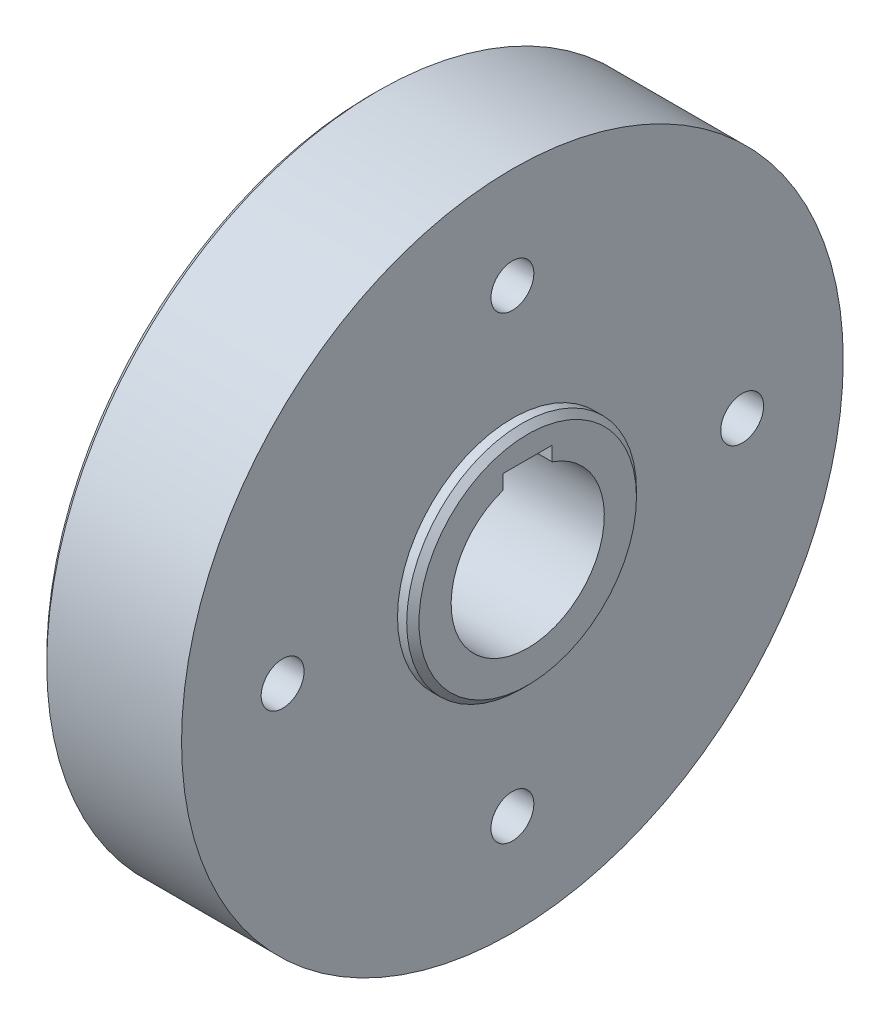
SolidWorks part; units mm, degrees
ref_plane "Front Plane" through (0, 0, 0) normal (0, 0, 1) x (1, 0, 0)
ref_plane "Top Plane" through (0, 0, 0) normal (0, 1, 0) x (1, 0, 0)
ref_plane "Right Plane" through (0, 0, 0) normal (1, 0, 0) x (0, 0, -1)
sketch "Sketch1" plane through (0, 0, 0) normal (0, 0, 1) x (1, 0, 0)
  line L0 (0, 0) -> (0, 15070.8085) construction
  line L1 (0, 0) -> (15070.8085, 0) construction
  line L2 (-40, 0) -> (40, 0)
  line L3 (-40, 25) -> (40, 25)
  line L4 (40, 108) -> (15, 108)
  line L5 (-40, 50) -> (15, 50)
  line L6 (15, 108) -> (15, 50)
  line L7 (-40, 50) -> (-40, 25)
  line L8 (40, 108) -> (40, 37.5)
  line L9 (40, 37.5) -> (45, 37.5)
  line L10 (45, 37.5) -> (45, 25)
  line L11 (45, 25) -> (40, 25)
  point P7 (0, 0)
  point P10 (0, 25)
  dimension "D1" = 80
  dimension "D2" = 50
  dimension "D3" = 216
  dimension "D4" = 25
  dimension "D5" = 100
  dimension "D6" = 75
  dimension "D7" = 5
revolve "Revolve1" add sketch "Sketch1" angle 360 about L2
sketch "Sketch2" plane through (40, 0, 0) normal (1, 0, 0) x (0, 0, -1)
  circle A0 centre (0, 0) radius 75 construction
  point P4 (0, 75)
  point P11 (75, 0)
  point P12 (0, -75)
  point P13 (-75, 0)
  dimension "D1" = 150
  dimension "D2" = 4
hole_wizard "M16x2.0 Tapped Hole1" positions "Sketch2" profile "Sketch3" tap size "M16x2.0" standard "ANSI Metric" end condition through all
sketch "Sketch3" plane through (40, 0, 75) normal (0, 1, 0) x (0, 0, -1)
  line L0 (0, 0) -> (0, 80)
  line L1 (0, 80) -> (7, 80)
  line L2 (7, 80) -> (7, 0)
  line L5 (7, 0) -> (0, 0)
  line L11 (0, -6.35) -> (0, 107.95) construction
  dimension "Thru Tap Drill Dia." = 14
  dimension "Thru Tap Drill Depth" = 80
cosmetic thread "Hole Thread1" parameters "D2"=16
cosmetic thread "Hole Thread2" parameters "D2"=16
cosmetic thread "Hole Thread3" parameters "D2"=16
cosmetic thread "Hole Thread4" parameters "D2"=16
sketch "Sketch4" plane through (0, 0, 0) normal (0, 0, 1) x (1, 0, 0)
  line L0 (15, 108) -> (-6, 108)
  line L1 (-6, 108) -> (-6, 100)
  line L2 (-6, 100) -> (15, 100)
  line L3 (15, 108) -> (15, -108) construction
  line L4 (15, 100) -> (15, 108)
  line L5 (0, 0) -> (133.487, 0) construction
  line L6 (40, -108) -> (40, 108) construction
  dimension "D1" = 200
  dimension "D2" = 46
revolve "Revolve2" add sketch "Sketch4" angle 360 about L5
sketch "Sketch5" plane through (0, 0, 0) normal (0, 0, 1) x (1, 0, 0)
  line L0 (-40, 0) -> (45, 0) construction
  line L1 (-40, 50) -> (-40, -50) construction
  line L2 (45, -37.5) -> (45, 37.5) construction
  line L4 (-40, 0) -> (45, 0)
  line L5 (-40, 0) -> (-40, 27.55)
  line L6 (-40, 27.55) -> (45, 28.4)
  line L7 (45, 0) -> (45, 28.4)
  line L8 (-40, -25) -> (45, -25) construction
  dimension "D1" = 53.4
  dimension "D2" = 52.55
extrude "Cut-Extrude1" cut sketch "Sketch5" against normal mid plane 16
chamfer "Chamfer2" distance 2 angle 45 4 edges at (45, 0, 37.5) (15, 0, 50) (-40, 0, 50) (-6, 0, 108)
